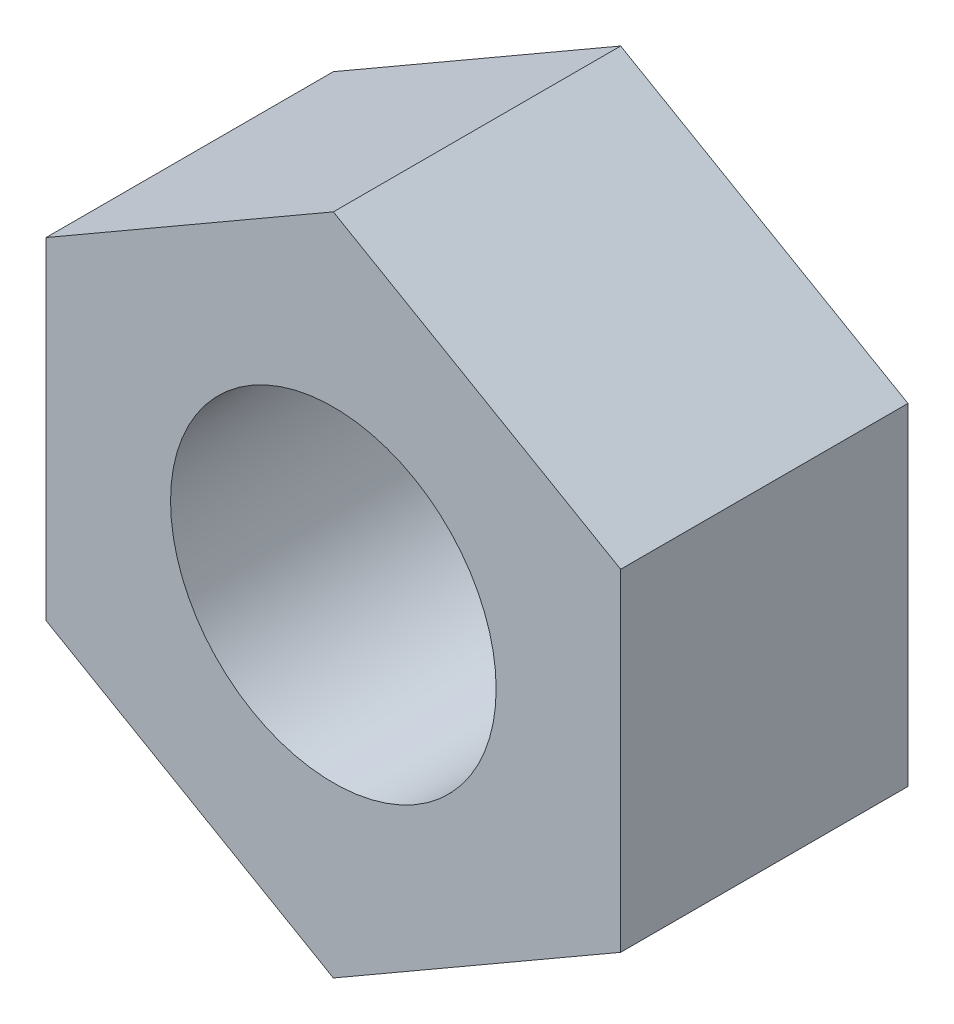
SolidWorks part; units mm, degrees
ref_plane "前视基准面" through (0, 0, 0) normal (0, 0, 1) x (1, 0, 0)
ref_plane "上视基准面" through (0, 0, 0) normal (0, 1, 0) x (1, 0, 0)
ref_plane "右视基准面" through (0, 0, 0) normal (1, 0, 0) x (0, 0, -1)
sketch "草图1" plane through (0, 0, 0) normal (0, 0, 1) x (1, 0, 0)
  line L1 (6, -3.4641) -> (6, 3.4641)
  line L2 (6, 3.4641) -> (0, 6.9282)
  line L3 (0, 6.9282) -> (-6, 3.4641)
  line L4 (-6, 3.4641) -> (-6, -3.4641)
  line L5 (-6, -3.4641) -> (0, -6.9282)
  line L6 (0, -6.9282) -> (6, -3.4641)
  circle A0 centre (0, 0) radius 6 construction
  dimension "D1" = 12
extrude "凸台-拉伸1" add sketch "草图1" along normal blind 6
hole_wizard "M8 螺纹孔2" positions "草图2" profile "草图3" tap size "M8" standard "GB" end condition through all
sketch "草图2" plane through (0, 0, 6) normal (0, 0, 1) x (1, 0, 0)
  point P0 (0, 0)
sketch "草图3" plane through (0, 0, 6) normal (1, 0, 0) x (0, -1, 0)
  line L0 (0, 0) -> (0, 6)
  line L1 (0, 6) -> (3.4, 6)
  line L2 (3.4, 6) -> (3.4, 0)
  line L5 (3.4, 0) -> (0, 0)
  line L11 (0, -6.35) -> (0, 107.95) construction
  dimension "通孔螺纹孔钻头直径" = 6.8
  dimension "通孔螺纹孔钻头深度" = 6
cosmetic thread "孔螺纹线1" parameters "D2"=8
